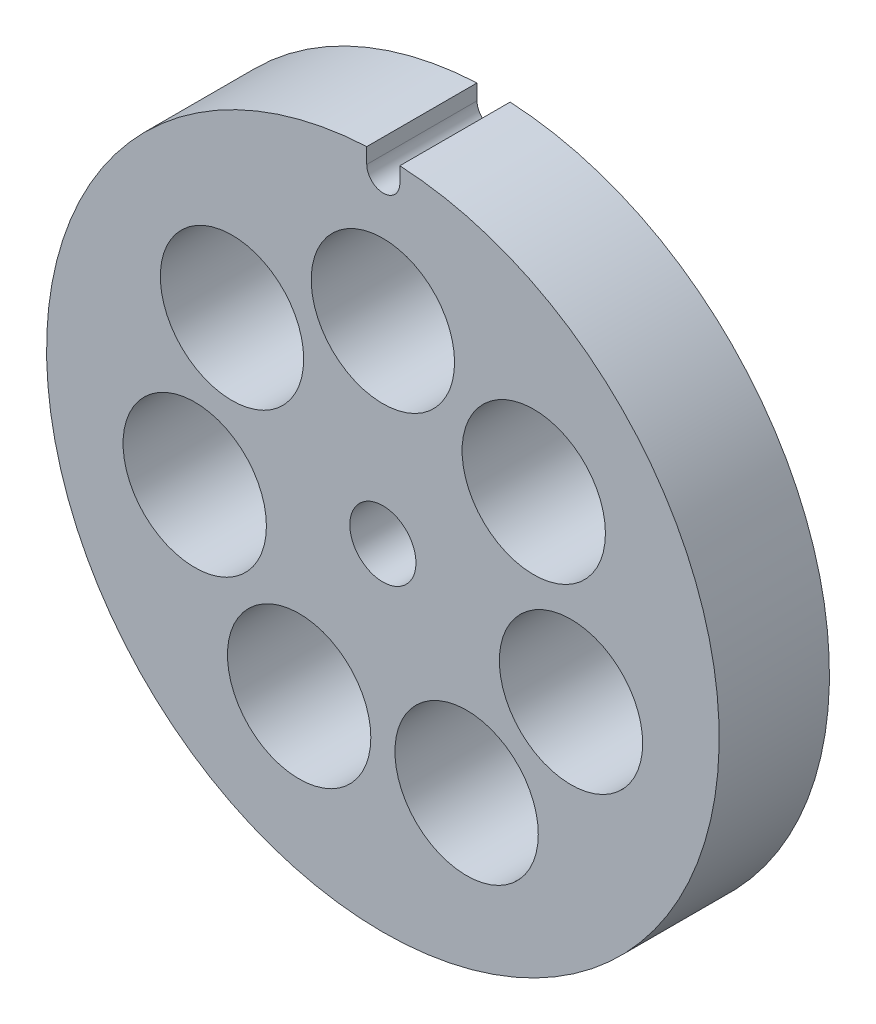
SolidWorks part; units mm, degrees
ref_plane "Płaszczyzna przednia" through (0, 0, 0) normal (0, 0, 1) x (1, 0, 0)
ref_plane "Płaszczyzna górna" through (0, 0, 0) normal (0, 1, 0) x (1, 0, 0)
ref_plane "Płaszczyzna prawa" through (0, 0, 0) normal (1, 0, 0) x (0, 0, -1)
sketch "Szkic1" plane through (0, 0, 0) normal (0, 0, 1) x (1, 0, 0)
  line L0 (-1.4635, 29.0613) -> (-1.4635, 30.4649)
  line L1 (1.5365, 29.0613) -> (1.5365, 30.4613)
  circle A0 centre (0, 0) radius 30.5
  circle A1 centre (0, 0) radius 3
  circle A2 centre (0, 17.5) radius 6.5
  circle A3 centre (13.6821, 10.9111) radius 6.5
  circle A4 centre (17.0612, -3.8941) radius 6.5
  circle A5 centre (7.593, -15.767) radius 6.5
  circle A6 centre (-7.593, -15.767) radius 6.5
  circle A7 centre (-17.0612, -3.8941) radius 6.5
  circle A8 centre (-13.6821, 10.9111) radius 6.5
  arc A9 (-1.4635, 29.0613) -> (1.5365, 29.0613) centre (0.0365, 29.0613) ccw
  point P21 (0, 0)
  point P22 (1.5365, 29.7613)
  dimension "D1" = 61
  dimension "D2" = 6
  dimension "D4" = 13
  dimension "D7" = 1.5
  dimension "D3" = 17.5
  dimension "D6" = 1.4
  dimension "D5" = 7
extrude "Dodanie-wyciągnięcie1" add sketch "Szkic1" along normal blind 10 contours A9 L0 A0 L1 A8 A7 A6 A5 A4 A3 A2 A1
